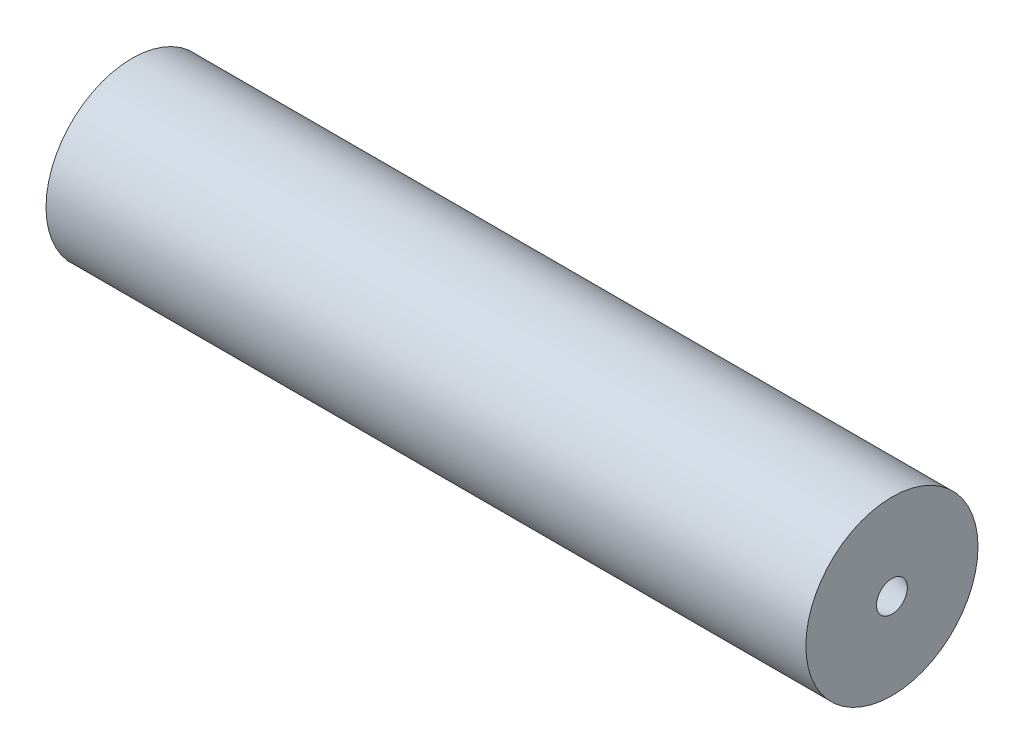
SolidWorks part; units mm, degrees
ref_plane "Front Plane" through (0, 0, 0) normal (0, 0, 1) x (1, 0, 0)
ref_plane "Top Plane" through (0, 0, 0) normal (0, 1, 0) x (1, 0, 0)
ref_plane "Right Plane" through (0, 0, 0) normal (1, 0, 0) x (0, 0, -1)
sketch "Sketch1" plane through (0, 0, 0) normal (0, 0, 1) x (1, 0, 0)
  line L0 (0, 12.7) -> (196.85, 12.7)
  line L1 (196.85, 12.7) -> (196.85, 26.162)
  line L2 (196.85, 26.162) -> (241.3, 26.162)
  line L3 (241.3, 26.162) -> (241.3, 0)
  line L6 (0, 12.7) -> (0, 31)
  line L8 (259.36, 10.7696) -> (259.36, 0)
  line L9 (259.36, 0) -> (241.3, 0)
  line L10 (0, 0) -> (298.2335, 0) construction
  line L11 (259.36, 10.7696) -> (273.6661, 5.5626)
  line L12 (273.6661, 5.5626) -> (273.6661, 31)
  line L14 (273.6661, 31) -> (0, 31)
  point P7 (273.6661, 32.8503)
  point P12 (259.36, 5.3848)
  dimension "D1" = 26.162
  dimension "D2" = 12.7
  dimension "D3" = 62
  dimension "D4" = 44.45
  dimension "D5" = 196.85
  dimension "D6" = 18.06
  dimension "D7" = 10.7696
  dimension "D8" = 5.5626
  dimension "D9" = 14.3061
revolve "Revolve1" add sketch "Sketch1" angle 360 about L10
sketch "Sketch3" plane through (241.3, 0, 0) normal (-1, 0, 0) x (0, 0, 1)
  circle A1 centre (0, 0) radius 6.477 construction
  circle A2 centre (0, 6.477) radius 0.8065
  circle A3 centre (4.5799, 4.5799) radius 0.8065
  circle A4 centre (6.477, 0) radius 0.8065
  circle A5 centre (4.5799, -4.5799) radius 0.8065
  circle A6 centre (0, -6.477) radius 0.8065
  circle A7 centre (-4.5799, -4.5799) radius 0.8065
  circle A8 centre (-6.477, 0) radius 0.8065
  circle A9 centre (-4.5799, 4.5799) radius 0.8065
  point P21 (0, 0)
  dimension "D1" = 12.954
  dimension "D2" = 1.6129
  dimension "D3" = 8
extrude "Cut-Extrude1" cut sketch "Sketch3" against normal up to next
